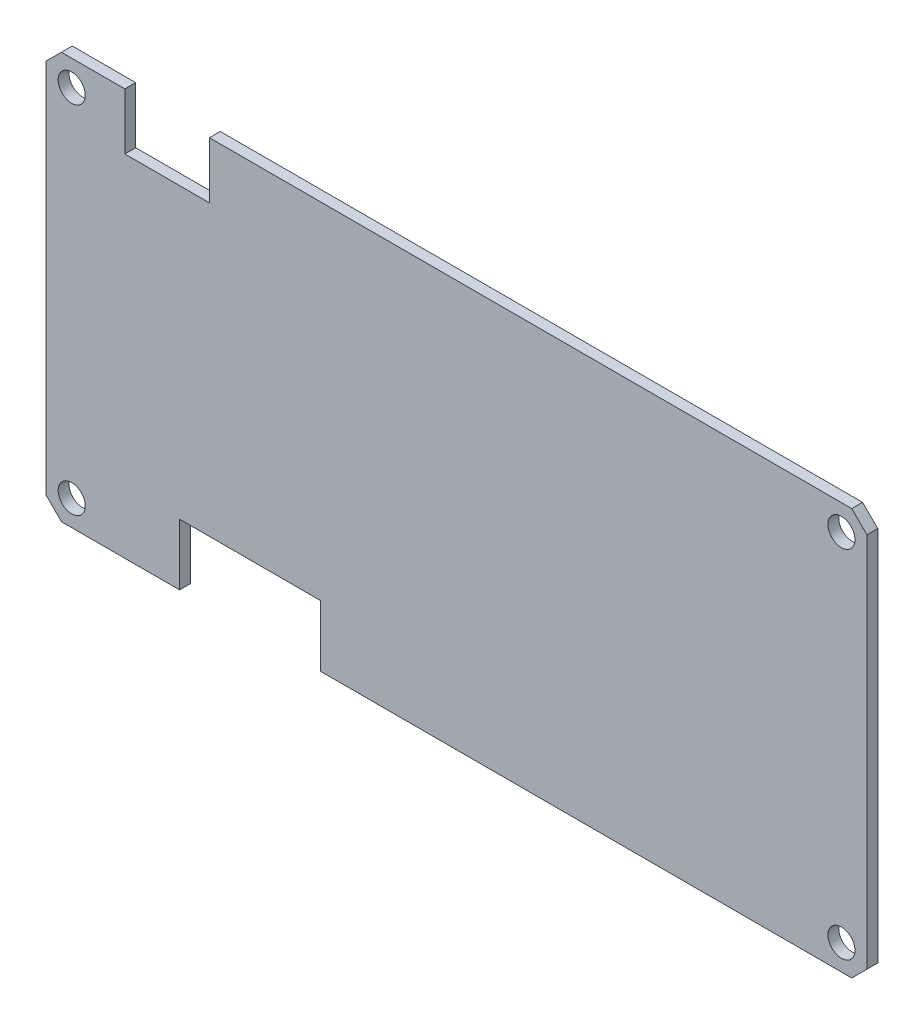
SolidWorks part; units mm, degrees
ref_plane "Front Plane" through (0, 0, 0) normal (0, 0, 1) x (1, 0, 0)
ref_plane "Top Plane" through (0, 0, 0) normal (0, 1, 0) x (1, 0, 0)
ref_plane "Right Plane" through (0, 0, 0) normal (1, 0, 0) x (0, 0, -1)
sketch "Sketch1" plane through (0, 0, 0) normal (0, 0, 1) x (1, 0, 0)
  line L1 (0, -18.75) -> (-33.8, -18.75)
  line L2 (0, -18.75) -> (0, 18.75)
  line L3 (0, 18.75) -> (-33.8, 18.75)
  line L4 (-33.8, -18.75) -> (-33.8, 18.75)
  line L5 (-31.8, -4.9) -> (-31.8, -14.1) construction
  dimension "D1" = 37.5
  dimension "D2" = 2
extrude "Boss-Extrude-NoAnt" add sketch "Sketch1" along normal blind 1
sketch "Sketch2" plane through (0, 0, 0) normal (0, 0, 1) x (1, 0, 0)
  line L1 (0, 18.75) -> (41.9, 18.75)
  line L2 (0, 18.75) -> (0, -18.75)
  line L3 (0, -18.75) -> (41.9, -18.75)
  line L4 (41.9, 18.75) -> (41.9, -18.75)
  line L5 (-33.8, -18.75) -> (0, -18.75) construction
  dimension "D1" = 41.9
extrude "Boss-Extrude-Ant" add sketch "Sketch2" along normal up to surface (1 mm away) up to face at (-16.9, 0, 1)
sketch "Sketch3" plane through (0, 0, 0) normal (0, 0, -1) x (-1, 0, 0)
  line L0 (31.45, -16.4) -> (-39.55, -16.4) construction
  line L1 (-39.55, -16.4) -> (-39.55, 16.4) construction
  line L2 (-39.55, 16.4) -> (31.45, 16.4) construction
  line L3 (31.45, 16.4) -> (31.45, -16.4) construction
  line L4 (-41.9, 18.75) -> (33.8, 18.75) construction
  line L5 (31.45, 16.4) -> (31.45, 18.75) construction
  line L6 (31.45, 16.4) -> (33.8, 16.4) construction
  line L7 (33.8, 18.75) -> (33.8, -18.75) construction
  line L8 (-39.55, 16.4) -> (-41.9, 16.4) construction
  line L9 (-41.9, -18.75) -> (-41.9, 18.75) construction
  line L10 (31.45, -16.4) -> (31.45, -18.75) construction
  line L11 (33.8, -18.75) -> (-41.9, -18.75) construction
  circle A0 centre (31.45, -16.4) radius 1.25
  circle A1 centre (-39.55, -16.4) radius 1.25
  circle A2 centre (-39.55, 16.4) radius 1.25
  circle A3 centre (31.45, 16.4) radius 1.25
  dimension "D1" = 2.5
  dimension "D2" = 2.35
extrude "Holes" cut sketch "Sketch3" against normal through all
sketch "Sketch4" plane through (0, 0, 0) normal (0, 0, -1) x (-1, 0, 0)
  line L0 (-41.9, 18.75) -> (-40.5, 18.75)
  line L1 (-41.9, 18.75) -> (33.8, 18.75) construction
  line L2 (-40.5, 18.75) -> (-41.9, 17.35)
  line L3 (-41.9, -18.75) -> (-41.9, 18.75) construction
  line L4 (-41.9, 17.35) -> (-41.9, 18.75)
  line L5 (-41.4626, 16.2552) -> (-39.3888, 18.3289) construction
  line L6 (-4.05, 18.75) -> (-4.05, -18.75) construction
  line L7 (33.8, -18.75) -> (-41.9, -18.75) construction
  line L8 (-41.9, 0) -> (33.8, 0) construction
  line L9 (33.8, 18.75) -> (33.8, -18.75) construction
  line L10 (-41.9, -17.35) -> (-41.9, -18.75)
  line L11 (-40.5, -18.75) -> (-41.9, -17.35)
  line L12 (-41.9, -18.75) -> (-40.5, -18.75)
  line L13 (33.8, -18.75) -> (32.4, -18.75)
  line L14 (32.4, -18.75) -> (33.8, -17.35)
  line L15 (33.8, -17.35) -> (33.8, -18.75)
  line L16 (33.8, 17.35) -> (33.8, 18.75)
  line L17 (32.4, 18.75) -> (33.8, 17.35)
  line L18 (33.8, 18.75) -> (32.4, 18.75)
  circle A0 centre (-39.55, 16.4) radius 1.25 construction
  dimension "D1" = 1.4
  dimension "D2" = 1.0835
extrude "Corners" cut sketch "Sketch4" against normal through all
sketch "Sketch5" plane through (0, 0, 1) normal (0, 0, 1) x (1, 0, 0)
  line L0 (-32.4, -18.75) -> (40.5, -18.75) construction
  line L1 (-21.5, -18.75) -> (-8.5, -18.75)
  line L2 (-21.5, -18.75) -> (-21.5, -13.1)
  line L3 (-21.5, -13.1) -> (-8.5, -13.1)
  line L4 (-8.5, -18.75) -> (-8.5, -13.1)
  line L5 (-33.8, 17.35) -> (-33.8, -17.35) construction
  dimension "D1" = 25.3
  dimension "D2" = 5.65
  dimension "D3" = 13
extrude "Cut-Extrude1" cut sketch "Sketch5" against normal through all
sketch "Sketch6" plane through (0, 0, 0) normal (0, 0, -1) x (-1, 0, 0)
  line L0 (-40.5, 18.75) -> (32.4, 18.75) construction
  line L1 (18.75, 18.75) -> (26.55, 18.75)
  line L2 (18.75, 18.75) -> (18.75, 13.55)
  line L3 (18.75, 13.55) -> (26.55, 13.55)
  line L4 (26.55, 18.75) -> (26.55, 13.55)
  line L5 (33.8, 17.35) -> (33.8, -17.35) construction
  dimension "D1" = 7.25
  dimension "D2" = 15.05
  dimension "D3" = 5.2
extrude "Cut-Extrude2" cut sketch "Sketch6" against normal through all
